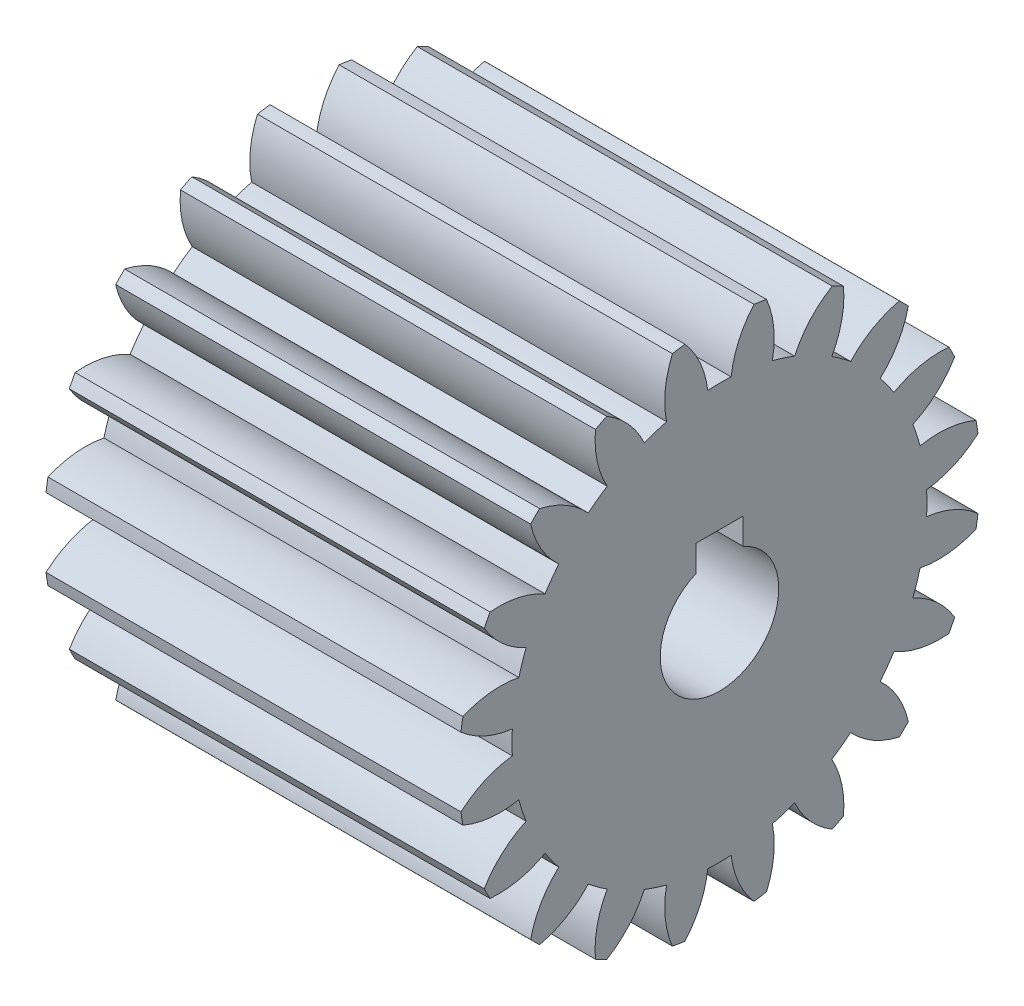
SolidWorks part; units mm, degrees
ref_plane "Plane1" through (0, 0, 0) normal (0, 0, 1) x (1, 0, 0)
ref_plane "Plane2" through (0, 0, 0) normal (0, 1, 0) x (1, 0, 0)
ref_plane "Plane3" through (0, 0, 0) normal (1, 0, 0) x (0, 0, -1)
sketch "HoldingSke" plane through (0, 0, 0) normal (0, 1, 0) x (1, 0, 0)
  line L0 (0, 0) -> (0.4698, -0.171)
  line L1 (-15, 0) -> (100, 0) construction
  line L2 (0, 0) -> (-2.1039, 2.3779)
  line L3 (0, 0) -> (-11.863, 4.5341)
  line L4 (0, 0) -> (8.1152, 2.9537)
  line L5 (0, 0) -> (-46.8476, -17.4728)
  line L6 (0, 0) -> (-29.0137, -19.5756)
  line L7 (-2.1039, 2.3779) -> (8.6586, 51.2059)
  line L8 (-76.2, 54.61) -> (-74.4, 54.61)
  line L9 (-71.009, 38.7566) -> (-53.1078, 45.2721)
  line L10 (-76.2, 71.12) -> (104.1128, 71.12)
  line L11 (0, 0) -> (-35, 0)
  line L12 (-76.2, 101.6) -> (-76.133, 101.6)
  line L13 (24.9733, 27.94) -> (52.9518, 28.4284)
  line L14 (24.9733, 27.94) -> (24.9743, 27.94)
  line L15 (24.9733, 27.94) -> (100.4006, 29.5858)
  line L16 (-63.627, -2) -> (-12.827, -2)
  circle A0 centre (0, 0) radius 5
  circle A1 centre (0, 0) radius 17.499
  circle A2 centre (0, 0) radius 37.5
  circle A3 centre (0, 0) radius 5
  dimension "MHD" = 34.998
  dimension "Hub_dia" = 75
  dimension "Bore" = 10
  dimension "MBD" = 10
  dimension "Num_teeth" = 20
  dimension "Pitch" = 0.5
  dimension "Overall_len" = 50
  dimension "Show_teeth" = 20
  dimension "Thickness" = 35
  dimension "OAL" = 50.0001
  dimension "T_dim" = 1.8
  dimension "Ap" = 20
  dimension "H" = 19.05
  dimension "Pitch_radius" = 180.3128
  dimension "Width" = 35
  dimension "Backlash" = 0.067
  dimension "Addendum_fac" = 1
  dimension "Dedendum_fac" = 1.25
  dimension "Clearance_fac" = 0.25
  dimension "Dedendum_add" = 0.001
  dimension "Module" = 2
sketch "BasProSke" plane through (0, 0, 0) normal (0, 1, 0) x (1, 0, 0)
  line L0 (-10, 0) -> (60, 0) construction
  line L1 (0, 0) -> (0, 22)
  line L2 (0, 0) -> (35, 0)
  line L3 (35, 0) -> (35, 22)
  line L4 (35, 22) -> (0, 22)
  dimension "Thickness" = 35
  dimension "Diameter" = 44
revolve "Base-Revolve" add sketch "BasProSke" angle 360 about L0
sketch "TooCutSke" plane through (0, 0, 0) normal (1, 0, 0) x (0, 0, -1)
  line L1 (0, 0) -> (0, 107) construction
  line L2 (0, 0) -> (-1.6864, 19.9288) construction
  line L3 (0, 0) -> (-6.2409, 39.4033) construction
  line L4 (-1.6864, 19.9288) -> (-3.1204, 19.7016) construction
  arc A0 (0.9862, 17.4712) -> (-0.9862, 17.4712) centre (0, 0) ccw
  arc A1 (2.9329, 21.8293) -> (-2.9329, 21.8293) centre (0, 0) ccw
  circle A2 centre (0, 0) radius 20 construction
  circle A3 centre (0, 0) radius 18.7939 construction
  arc A4 (-0.9862, 17.4712) -> (-2.9329, 21.8293) centre (-8.9313, 16.536) ccw
  arc A5 (2.9329, 21.8293) -> (0.9862, 17.4712) centre (8.9313, 16.536) ccw
  dimension "Root_dia" = 34.998
  dimension "Overcut_dia" = 44.0508
  dimension "Pitch_dia" = 40
  dimension "Base_dia" = 37.5877
  dimension "Flank_rad" = 8
  dimension "Half_ang" = 9
  dimension "Half_CT" = 1.4519
extrude "ToothCut" cut sketch "TooCutSke" along normal through all
fillet "Breaks" [suppressed] radius 0.04
fillet "RootFillets" [suppressed] radius 0.501
pattern_circular "TeethCuts" count 20 every 18 about axis through (-10, 0, 0) along (1, 0, 0) of "ToothCut", "RootFillets", "Breaks"
sketch "HubNeaOneSke" plane through (0, 0, 0) normal (-1, 0, 0) x (0, 0, 1)
  circle A0 centre (0, 0) radius 17.499
  dimension "Diameter" = 34.998
extrude "HubNearOne" [suppressed] add sketch "HubNeaOneSke" along normal blind 15.0001
sketch "HubNeaBotSke" plane through (0, 0, 0) normal (-1, 0, 0) x (0, 0, 1)
  circle A0 centre (0, 0) radius 17.499
  dimension "Diameter" = 34.998
extrude "HubNearBoth" [suppressed] add sketch "HubNeaBotSke" along normal blind 7.5
ref_plane "FarPln" through (35, 0, 0) normal (1, 0, 0) x (0, 0, -1)
sketch "HubFarSke" plane through (35, 0, 0) normal (1, 0, 0) x (0, 0, -1)
  circle A0 centre (0, 0) radius 17.499
  dimension "Diameter" = 34.998
extrude "HubFar" [suppressed] add sketch "HubFarSke" along normal blind 7.5
sketch "BorSke" plane through (0, 0, 0) normal (1, 0, 0) x (0, 0, -1)
  circle A0 centre (0, 0) radius 5
  dimension "Diameter" = 10
extrude "Bore" cut sketch "BorSke" along normal mid plane 100.0001
sketch "KeySke" plane through (0, 0, 0) normal (1, 0, 0) x (0, 0, -1)
  line L0 (-2, 0) -> (-2, 6.8)
  line L1 (-2, 6.8) -> (2, 6.8)
  line L2 (2, 6.8) -> (2, 0)
  line L3 (0, 0) -> (0, 34) construction
  line L4 (-2, 0) -> (2, 0)
  dimension "Offset" = 6.8
  dimension "Width" = 4
extrude "Keyway" cut sketch "KeySke" along normal mid plane 100.0001
pattern_circular "Keyway2" [suppressed] count 2 every 90 about axis through (-10, 0, 0) along (1, 0, 0)
equation "' \"Module@HoldingSke\" = 6.35"
equation "' \"Num_teeth@HoldingSke\" = 12"
equation "' \"Ap@HoldingSke\" =  20"
equation "' \"Ap@HoldingSke\" = 20"
equation "' \"Width@HoldingSke\" = 0.5 * 25.4"
equation "' \"Hub_dia@HoldingSke\"= 1 * 25.4"
equation "' \"Hub_dia@HoldingSke\" = 1 * 25.4"
equation "' \"Overall_len@HoldingSke\" = 1.0 * 25.4"
equation "' \"Bore@HoldingSke\" = 0.75 * 25.4"
equation "' \"T_dim@HoldingSke\" = 0.1 * 25.4"
equation "' \"Width@KeySke\" = 0.25 * 25.4"
equation "' \"Show_teeth@HoldingSke\" = 13"
equation "' \"Backlash@HoldingSke\" = 0.009 * 25.4"
equation "' \"Addendum_fac@HoldingSke\" = 1.0"
equation "' \"Dedendum_fac@HoldingSke\" = 1.25"
equation "' \"Dedendum_add@HoldingSke\" = 0.00005 * 25.4"
equation "' \"Clearance_fac@HoldingSke\" = 0.25"
equation "\"Pitch@HoldingSke\" = 1 / \"Module@HoldingSke\""
equation "\"Overcut_dia@TooCutSke\" = (\"Num_teeth@HoldingSke\" + 2 * \"Addendum_fac@HoldingSke\") / \"Pitch@HoldingSke\" + 0.002 * 25.4"
equation "\"Pitch_dia@TooCutSke\" = \"Num_teeth@HoldingSke\" / \"Pitch@HoldingSke\""
equation "\"Base_dia@TooCutSke\" = \"Num_teeth@HoldingSke\" / \"Pitch@HoldingSke\" * cos((\"Ap@HoldingSke\"  * 3.14159265 / 180))"
equation "\"Root_dia@TooCutSke\" = (\"Num_teeth@HoldingSke\" + 2) / \"Pitch@HoldingSke\" - 2 * (\"Addendum_fac@HoldingSke\" + \"Dedendum_fac@HoldingSke\") / \"Pitch@HoldingSke\" - \"Dedendum_add@HoldingSke\" * 2"
equation "\"Half_ang@TooCutSke\" = 180 / \"Num_teeth@HoldingSke\""
equation "\"Half_CT@TooCutSke\" = \"Num_teeth@HoldingSke\" / \"Pitch@HoldingSke\" * sin((3.14159265 / 2 / \"Num_teeth@HoldingSke\")) / 2 - 7 * \"Backlash@HoldingSke\" / 4"
equation "\"Flank_rad@TooCutSke\" = \"Num_teeth@HoldingSke\" / \"Pitch@HoldingSke\" / 5"
equation "\"Radius@RootFillets\" = \"Clearance_fac@HoldingSke\" / \"Pitch@HoldingSke\" + \"Dedendum_add@HoldingSke\""
equation "\"Break_rad@Breaks\" = 0.02 / \"Pitch@HoldingSke\""
equation "\"Thickness@HoldingSke\" = \"Width@HoldingSke\""
equation "\"OAL@HoldingSke\" = \"Thickness@HoldingSke\""
equation "\"MHD@HoldingSke\" = (\"Num_teeth@HoldingSke\" + 2) / \"Pitch@HoldingSke\" - 2 * (\"Addendum_fac@HoldingSke\" + \"Dedendum_fac@HoldingSke\")  / \"Pitch@HoldingSke\" - \"Dedendum_add@HoldingSke\" * 2"
equation "\"MBD@HoldingSke\" = (\"Num_teeth@HoldingSke\" + 2) / \"Pitch@HoldingSke\" - 2 * (\"Addendum_fac@HoldingSke\" + \"Dedendum_fac@HoldingSke\")  / \"Pitch@HoldingSke\" - \"Dedendum_add@HoldingSke\" * 2 - 0.002 * 25.4"
equation "\"MHD@HoldingSke\" = ((sgn( \"MHD@HoldingSke\" - \"Hub_dia@HoldingSke\" )-1)*( \"MHD@HoldingSke\" - \"Hub_dia@HoldingSke\" ))/-2+ \"Hub_dia@HoldingSke\""
equation "\"MBD@HoldingSke\" = ((sgn( \"MBD@HoldingSke\" - \"Bore@HoldingSke\" )-1)*( \"MBD@HoldingSke\" - \"Bore@HoldingSke\" ))/-2+ \"Bore@HoldingSke\""
equation "\"OAL@HoldingSke\" = ((sgn( \"OAL@HoldingSke\" - \"Overall_len@HoldingSke\" )+1)*( \"OAL@HoldingSke\" - \"Overall_len@HoldingSke\" ))/2 + \"Overall_len@HoldingSke\" + 0.000002 * 25.4"
equation "\"Num_teeth@TeethCuts\" = int( \"Show_teeth@HoldingSke\" ) + 1"
equation "\"Num_teeth@TeethCuts\" = ((sgn( \"Num_teeth@TeethCuts\" - \"Num_teeth@HoldingSke\" )-1)*( \"Num_teeth@TeethCuts\" - \"Num_teeth@HoldingSke\" ))/-2+ \"Num_teeth@HoldingSke\""
equation "\"Num_teeth@TeethCuts\" = ((sgn( \"Num_teeth@TeethCuts\" - 2.0)+1)*( \"Num_teeth@TeethCuts\" - 2.0))/2 +2.0"
equation "\"Angle@TeethCuts\" = 360.0 / \"Num_teeth@HoldingSke\""
equation "\"Diameter@BasProSke\" = (\"Num_teeth@HoldingSke\" + 2 * \"Addendum_fac@HoldingSke\") / \"Pitch@HoldingSke\""
equation "\"Thickness@BasProSke\"  = \"Thickness@HoldingSke\""
equation "' \"Fillet_rad@BasProSke\" =  \"Thickness@HoldingSke\" * 0.05"
equation "' \"Fillet_rad@BasProSke\" = \"Thickness@HoldingSke\" * 0.05"
equation "\"MHD@HoldingSke\" = ((sgn( \"MHD@HoldingSke\" - \"Root_dia@TooCutSke\" )-1)*( \"MHD@HoldingSke\" - \"Root_dia@TooCutSke\" ))/-2+ \"Root_dia@TooCutSke\""
equation "\"Diameter@HubNeaOneSke\" = \"MHD@HoldingSke\""
equation "\"Length@HubNearOne\" = \"OAL@HoldingSke\" - \"Thickness@BasProSke\""
equation "\"Diameter@HubNeaBotSke\" = \"MHD@HoldingSke\""
equation "\"Length@HubNearBoth\" = ( \"OAL@HoldingSke\" - \"Thickness@BasProSke\" ) / 2.0"
equation "\"Thickness@FarPln\" = \"Thickness@BasProSke\""
equation "\"Diameter@HubFarSke\" = \"MHD@HoldingSke\""
equation "\"Length@HubFar\" = ( \"OAL@HoldingSke\" - \"Thickness@BasProSke\" ) / 2.0"
equation "\"Diameter@BorSke\" = \"MBD@HoldingSke\""
equation "\"D1@Bore\" = \"OAL@HoldingSke\" * 2.0"
equation "\"D1@Keyway\" = \"OAL@HoldingSke\" * 2.0"
equation "\"Offset@KeySke\" = \"T_dim@HoldingSke\" + \"MBD@HoldingSke\" / 2.0"
